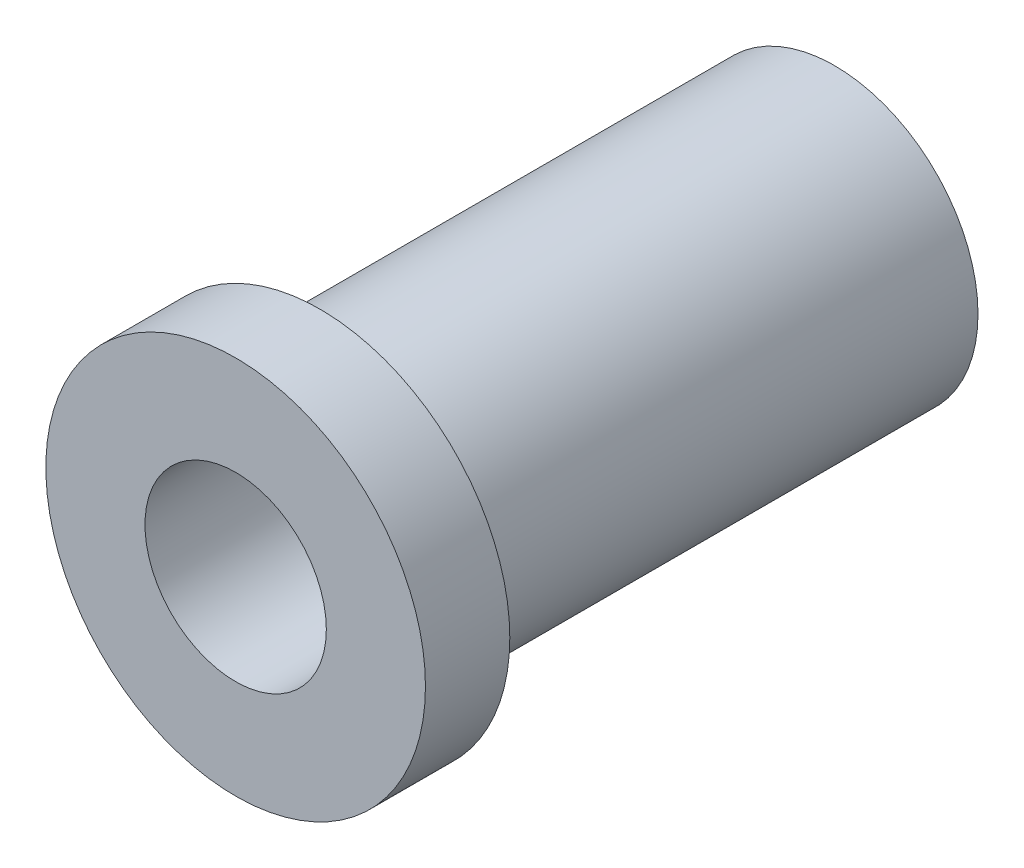
SolidWorks part; units mm, degrees
material "ABS"
ref_plane "前视基准面" through (0, 0, 0) normal (0, 0, 1) x (1, 0, 0)
ref_plane "上视基准面" through (0, 0, 0) normal (0, 1, 0) x (1, 0, 0)
ref_plane "右视基准面" through (0, 0, 0) normal (1, 0, 0) x (0, 0, -1)
sketch "草图1" plane through (0, 0, 0) normal (0, 0, 1) x (1, 0, 0)
  circle A0 centre (0, 0) radius 3.4
  circle A1 centre (0, 0) radius 2.15
  dimension "D1" = 6.8
  dimension "D2" = 4.3
extrude "凸台-拉伸1" add sketch "草图1" along normal blind 12.2 contours A0 A1
sketch "草图2" plane through (0, 0, 12.2) normal (0, 0, 1) x (1, 0, 0)
  circle A0 centre (0, 0) radius 2.15
  circle A1 centre (0, 0) radius 4.5
  dimension "D1" = 4.3
  dimension "D2" = 9
extrude "凸台-拉伸2" add sketch "草图2" along normal blind 2
